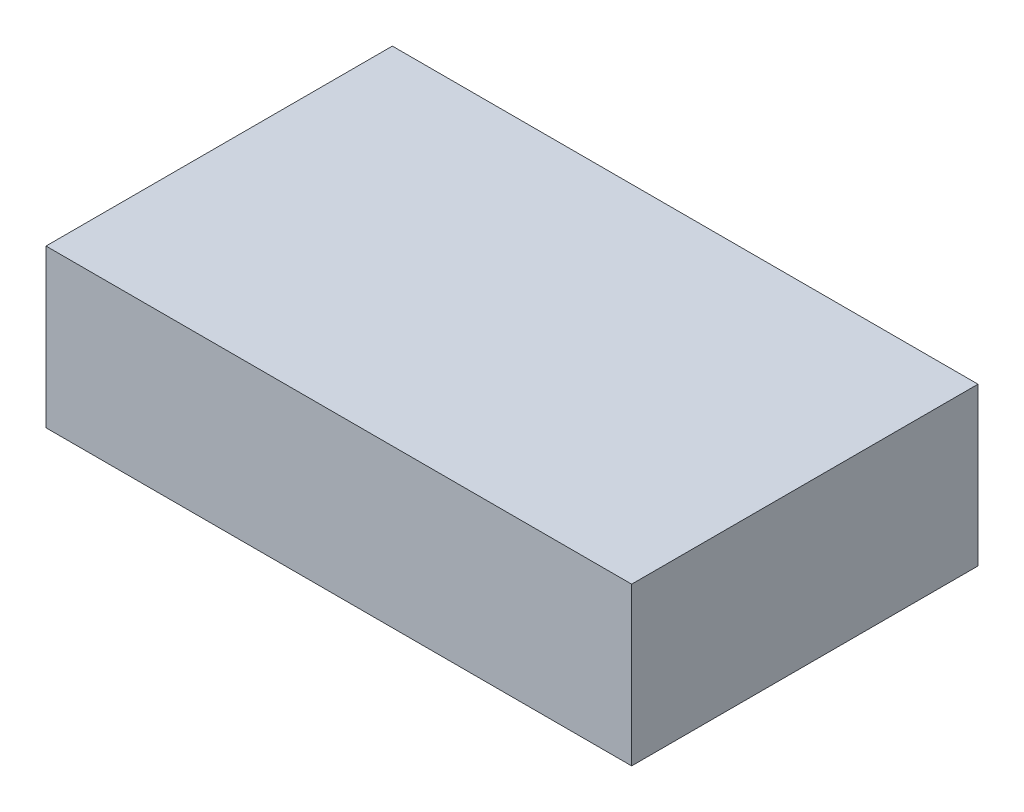
SolidWorks part; units mm, degrees
material "PET"
ref_plane "Front Plane" through (0, 0, 0) normal (0, 0, 1) x (1, 0, 0)
ref_plane "Top Plane" through (0, 0, 0) normal (0, 1, 0) x (1, 0, 0)
ref_plane "Right Plane" through (0, 0, 0) normal (1, 0, 0) x (0, 0, -1)
sketch "Sketch1" plane through (0, 0, 0) normal (0, 1, 0) x (1, 0, 0)
  line L1 (0, 0) -> (93, 0)
  line L2 (0, 0) -> (0, 55)
  line L3 (0, 55) -> (93, 55)
  line L4 (93, 0) -> (93, 55)
  dimension "D1" = 55
  dimension "D2" = 93
extrude "Boss-Extrude1" add sketch "Sketch1" along normal blind 25
shell "Shell1" thickness 2
